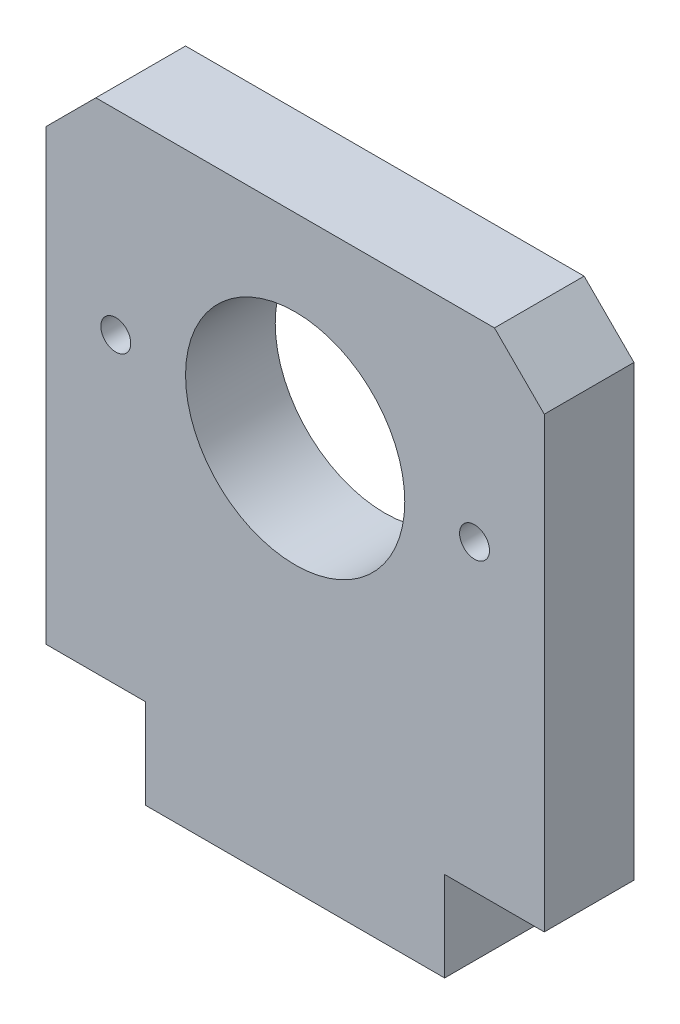
SolidWorks part; units mm, degrees
ref_plane "Front" through (0, 0, 0) normal (0, 0, 1) x (1, 0, 0)
ref_plane "Top" through (0, 0, 0) normal (0, 1, 0) x (1, 0, 0)
ref_plane "Right" through (0, 0, 0) normal (1, 0, 0) x (0, 0, -1)
sketch "Sketch1" plane through (0, 0, 0) normal (0, 0, 1) x (1, 0, 0)
  line L0 (25, 4.2267) -> (25, 50) construction
  line L1 (0, 0) -> (10, 0)
  line L2 (0, 0) -> (0, 45)
  line L3 (5, 50) -> (45, 50)
  line L4 (50, 0) -> (50, 45)
  line L5 (0, 45) -> (5, 50)
  line L6 (50, 45) -> (45, 50)
  line L7 (0, 30.4) -> (50, 30.4) construction
  line L8 (0, 4.2267) -> (50, 4.2267) construction
  line L10 (10, 0) -> (10, -9)
  line L11 (10, -9) -> (40, -9)
  line L12 (40, 0) -> (40, -9)
  line L13 (40, 0) -> (50, 0)
  circle A0 centre (25, 30.4) radius 11
  circle A1 centre (7, 30.4) radius 1.5
  circle A2 centre (43, 30.4) radius 1.5
  point P11 (25, 30.4)
  dimension "D6" = 22
  dimension "D8" = 3
  dimension "D1" = 135
  dimension "D2" = 5
  dimension "D4" = 50
  dimension "D5" = 30.4
  dimension "D7" = 18
  dimension "D3" = 50
  dimension "D9" = 9
  dimension "D10" = 30
extrude "Boss-Extrude1" add sketch "Sketch1" along normal blind 9
equation "\"material-thickness\" = 9mm"
equation "\"spindle-thread-height\" = 30.4mm ' Height from the base to the spindle for the stepper motor / Servo"
equation "\"spindle-thread-rbearing-diameter\" = 22mm ' Outer diameter of the rotational bearing"
equation "\"tab-width-large\" = 30mm ' Width of the large version of the Tab"
equation "\"D5@Sketch1\"=\"spindle-thread-height\""
equation "\"D6@Sketch1\"=\"spindle-thread-rbearing-diameter\""
equation "\"D1@Boss-Extrude1\"=\"material-thickness\""
equation "\"D9@Sketch1\"=\"material-thickness\""
equation "\"D10@Sketch1\"=\"tab-width-large\""
